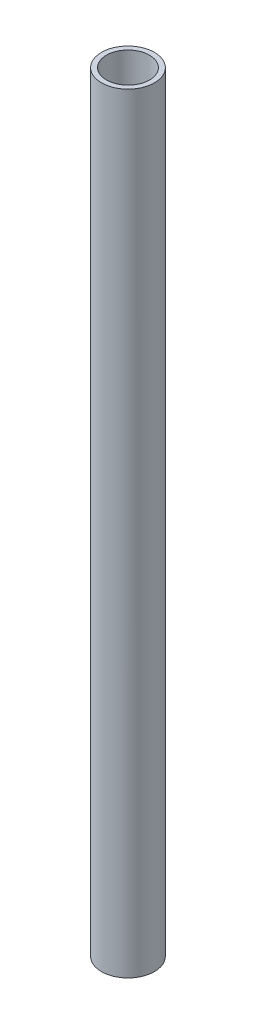
SolidWorks part; units mm, degrees
material "AISI 4130 Steel, annealed at 865C"
ref_plane "X-Y Datum" through (0, 0, 0) normal (0, 0, 1) x (1, 0, 0)
ref_plane "X-Z Datum" through (0, 0, 0) normal (0, 1, 0) x (1, 0, 0)
ref_plane "Y-Z Datum" through (0, 0, 0) normal (1, 0, 0) x (0, 0, -1)
sketch "Sketch1" plane through (0, 0, 0) normal (0, 1, 0) x (1, 0, 0)
  circle A0 centre (0, 0) radius 7.9375
  circle A1 centre (0, 0) radius 6.4643
  dimension "D1" = 1.4732
  dimension "D2" = 15.875
extrude "Boss-Extrude1" add sketch "Sketch1" along normal offset from surface (230.9855 mm away) 25.4
sketch "Sketch2" plane through (0, 0, 0) normal (1, 0, 0) x (0, 0, -1)
  line L0 (-3.175, 230.9855) -> (-3.175, 205.5855)
  line L1 (6.4643, 230.9855) -> (-6.4643, 230.9855) construction
  line L2 (3.175, 205.5855) -> (3.175, 230.9855)
  line L3 (3.175, 230.9855) -> (-3.175, 230.9855)
  line L5 (7.9375, 0) -> (7.9375, 230.9855) construction
  arc A0 (-3.175, 205.5855) -> (3.175, 205.5855) centre (0, 205.5855) ccw
  dimension "D1" = 6.35
  dimension "D2" = 25.4
  dimension "D3" = 4.7625
